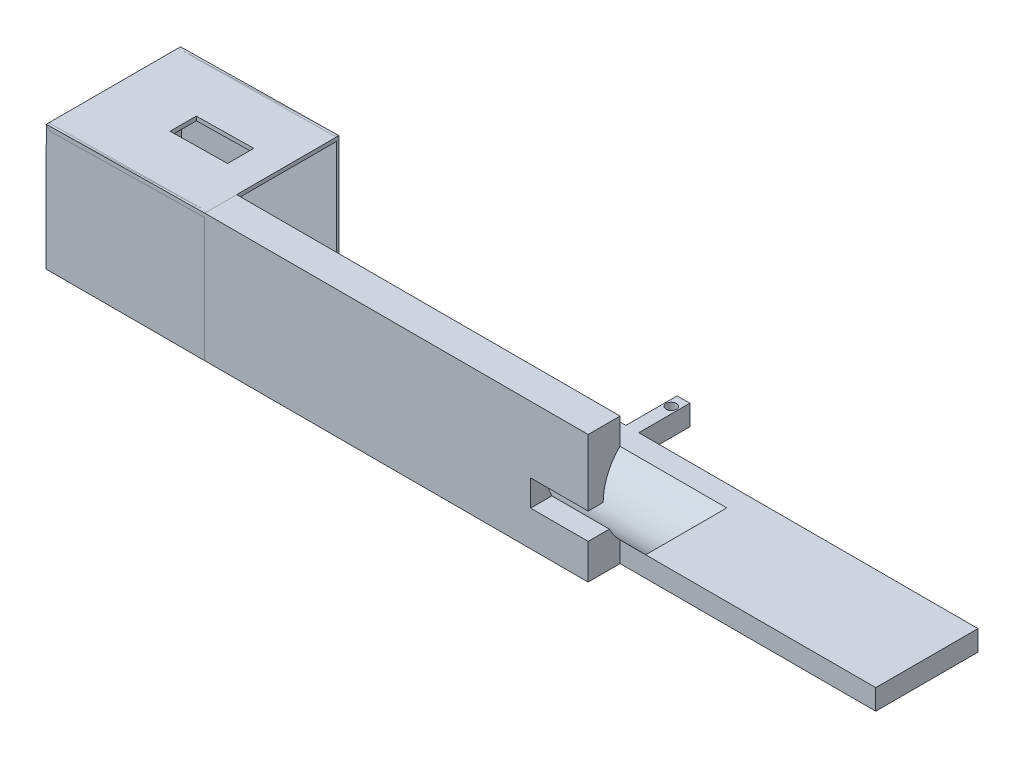
SolidWorks part; units mm, degrees
ref_plane "Front Plane" through (0, 0, 0) normal (0, 0, 1) x (1, 0, 0)
ref_plane "Top Plane" through (0, 0, 0) normal (0, 1, 0) x (1, 0, 0)
ref_plane "Right Plane" through (0, 0, 0) normal (1, 0, 0) x (0, 0, -1)
sketch "Sketch1" plane through (0, 0, 0) normal (0, 1, 0) x (1, 0, 0)
  line L1 (0, 0) -> (500, 0)
  line L2 (0, 0) -> (0, -80)
  line L3 (0, -80) -> (500, -80)
  line L4 (500, 0) -> (500, -80)
  dimension "D1" = 80
  dimension "D2" = 500
extrude "Boss-Extrude1" add sketch "Sketch1" along normal blind 16
sketch "Sketch9" plane through (0, 0, 80) normal (0, 0, 1) x (1, 0, 0)
  line L0 (0, 0) -> (500, 0) construction
  line L1 (300, 0) -> (0, 0)
  line L2 (300, 0) -> (300, 100)
  line L3 (300, 100) -> (0, 100)
  line L4 (0, 0) -> (0, 100)
  dimension "D1" = 100
  dimension "D2" = 300
extrude "Boss-Extrude5" add sketch "Sketch9" along normal blind 25
sketch "Sketch12" plane through (0, 0, 0) normal (-1, 0, 0) x (0, 0, 1)
  circle A0 centre (48.2576, 47.909) radius 45
  point P0 (40, 66.4351)
  dimension "D1" = 90
extrude "Cut-Extrude4" cut sketch "Sketch12" against normal blind 320
sketch "Sketch13" plane through (0, 0, 105) normal (0, 0, 1) x (1, 0, 0)
  line L0 (300, 0) -> (300, 100) construction
  line L1 (300, 48.0888) -> (255, 48.0888)
  line L2 (300, 48.0888) -> (300, 27.5888)
  line L3 (300, 27.5888) -> (255, 27.5888)
  line L4 (255, 48.0888) -> (255, 27.5888)
  dimension "D1" = 20.5
  dimension "D2" = 45
extrude "Cut-Extrude5" cut sketch "Sketch13" against normal blind 40
sketch "Sketch14" plane through (0, 0, 0) normal (0, 0, -1) x (-1, 0, 0)
  line L1 (-234.6, 16) -> (-224.6, 16)
  line L2 (-234.6, 16) -> (-234.6, 0)
  line L3 (-234.6, 0) -> (-224.6, 0)
  line L4 (-224.6, 16) -> (-224.6, 0)
  line L5 (-500, 0) -> (0, 0) construction
  line L6 (-300, 27.5888) -> (-300, 16.012) construction
  dimension "D1" = 65.4
  dimension "D2" = 10
extrude "Boss-Extrude6" add sketch "Sketch14" along normal blind 40
sketch "Sketch15" plane through (0, 16, 0) normal (0, 1, 0) x (1, 0, 0)
  circle A0 centre (229.494, 30.5626) radius 4
extrude "Cut-Extrude6" cut sketch "Sketch15" against normal blind 40
sketch "Sketch16" plane through (0, 0, 105) normal (0, 0, 1) x (1, 0, 0)
  line L0 (0, 100) -> (0, 0) construction
  line L1 (0, 0) -> (-140.5662, 0) construction
  line L2 (0, 100) -> (0, 97.02)
  line L3 (-121.0176, 0) -> (-123.9159, 0)
  line L4 (0, 100) -> (-123.9159, 98.2278)
  line L5 (-123.9159, 98.2278) -> (-123.9159, 0)
  line L6 (-121.0176, 0) -> (-121.0176, 94.9924)
  line L7 (-121.0176, 94.9924) -> (0, 97.02)
extrude "Boss-Extrude7" add sketch "Sketch16" against normal up to surface (105 mm away) up to face at (112.3, 8, 0)
sketch "Sketch17" plane through (0, 0, 105) normal (0, 0, 1) x (1, 0, 0)
  line L0 (-124.1432, 0) -> (0, 0)
  line L1 (0, 0) -> (0, 100)
  line L2 (0, 100) -> (-123.9159, 98.2278)
  line L3 (-123.9159, 98.2278) -> (-124.1432, 0)
extrude "Boss-Extrude8" add sketch "Sketch17" against normal blind 2 separate body
sketch "Sketch19" plane through (0, 0, 0) normal (0, 0, -1) x (-1, 0, 0)
  line L0 (0, 100) -> (0, 0)
  line L1 (0, 0) -> (124.1432, 0)
  line L2 (0, 100) -> (123.9159, 98.2278)
  line L3 (123.9159, 98.2278) -> (124.1432, 0)
extrude "Boss-Extrude10" add sketch "Sketch19" against normal blind 2 separate body
sketch "Sketch22" plane through (-1.4299, 99.9796, 0) normal (-0.0143, 0.9999, 0) x (0.9999, 0.0143, 0)
  line L0 (1.43, -105) -> (1.43, -80) construction
  line L1 (-68.57, -41.5653) -> (-23.57, -41.5653)
  line L2 (-68.57, -41.5653) -> (-68.57, -62.0653)
  line L3 (-68.57, -62.0653) -> (-23.57, -62.0653)
  line L4 (-23.57, -41.5653) -> (-23.57, -62.0653)
  dimension "D1" = 20.5
  dimension "D2" = 45
  dimension "D3" = 25
extrude "Cut-Extrude9" cut sketch "Sketch22" against normal blind 152
